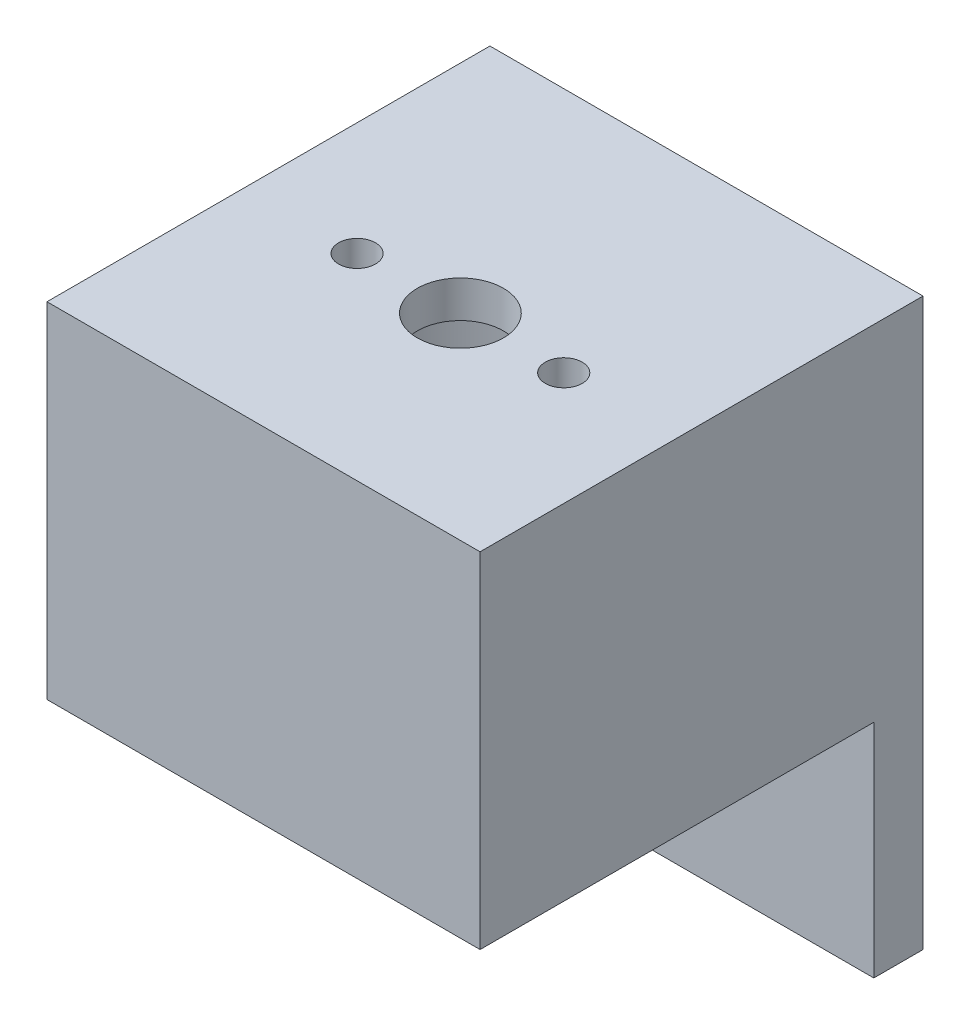
SolidWorks part; units mm, degrees
ref_plane "Спереди" through (0, 0, 0) normal (0, 0, 1) x (1, 0, 0)
ref_plane "Сверху" through (0, 0, 0) normal (0, 1, 0) x (1, 0, 0)
ref_plane "Справа" through (0, 0, 0) normal (1, 0, 0) x (0, 0, -1)
sketch "Эскиз1" plane through (0, 0, 0) normal (0, 0, 1) x (1, 0, 0)
  line L1 (-17.6, -21.5) -> (17.6, -21.5)
  line L2 (-17.6, -21.5) -> (-17.6, 21.5)
  line L3 (-17.6, 21.5) -> (17.6, 21.5)
  line L4 (17.6, -21.5) -> (17.6, 21.5)
  line L5 (-17.6, -21.5) -> (17.6, 21.5) construction
  line L6 (-17.6, 21.5) -> (17.6, -21.5) construction
  point P0 (0, 0)
  dimension "D1" = 35.2
  dimension "D2" = 43
extrude "Бобышка-Вытянуть1" add sketch "Эскиз1" along normal blind 4
sketch "Эскиз2" plane through (0, 0, 4) normal (0, 0, 1) x (1, 0, 0)
  line L0 (17.6, -21.5) -> (17.6, 21.5) construction
  line L1 (-17.6, 21.5) -> (17.6, 21.5)
  line L2 (-17.6, 21.5) -> (-17.6, -3.5)
  line L3 (-17.6, -3.5) -> (17.6, -3.5)
  line L4 (17.6, 21.5) -> (17.6, -3.5)
  dimension "D1" = 25
extrude "Бобышка-Вытянуть2" add sketch "Эскиз2" along normal blind 32
sketch "Эскиз4" plane through (0, -3.5, 0) normal (0, -1, 0) x (1, 0, 0)
  line L0 (17.6, 4) -> (-17.6, 36) construction
  line L1 (-17.6, 36) -> (17.6, 36) construction
  line L2 (-17.6, 36) -> (-17.6, 4) construction
  line L3 (17.6, 36) -> (-17.6, 4) construction
  circle A0 centre (0, 20) radius 12.5
extrude "Вырез-Вытянуть1" cut sketch "Эскиз4" against normal blind 32
sketch "Эскиз6" plane through (0, 0, 4) normal (0, 0, 1) x (1, 0, 0)
  line L0 (0, -3.5) -> (0, -21.5) construction
  line L1 (-17.6, -3.5) -> (17.6, -3.5) construction
  line L2 (-17.6, -21.5) -> (17.6, -21.5) construction
  circle A0 centre (0, -7.5) radius 2
  circle A1 centre (0, -17.5) radius 2
  dimension "D2" = 4
  dimension "D3" = 4
  dimension "D1" = 4
  dimension "D4" = 10
extrude "Вырез-Вытянуть2" cut sketch "Эскиз6" against normal blind 32
sketch "Эскиз7" plane through (0, 21.5, 0) normal (0, 1, 0) x (1, 0, 0)
  line L1 (-17.6, 0) -> (17.6, 0)
  line L2 (-17.6, 0) -> (-17.6, -36)
  line L3 (-17.6, -36) -> (17.6, -36)
  line L4 (17.6, 0) -> (17.6, -36)
extrude "Бобышка-Вытянуть3" add sketch "Эскиз7" along normal blind 3
sketch "Эскиз8" plane through (0, 24.5, 0) normal (0, 1, 0) x (1, 0, 0)
  line L0 (17.6, -4) -> (-17.6, -36) construction
  line L1 (-17.6, 0) -> (-17.6, -36) construction
  line L2 (17.6, 0) -> (-17.6, 0) construction
  line L3 (17.6, -36) -> (-17.6, -36) construction
  line L4 (17.6, -36) -> (17.6, -4) construction
  line L5 (17.6, -4) -> (-17.6, -4) construction
  line L6 (-17.6, -36) -> (-17.6, -4) construction
  line L7 (17.6, -36) -> (-17.6, -4) construction
  line L8 (-17.6, -20) -> (17.6, -20) construction
  line L9 (0, -20) -> (8.4, -20) construction
  line L10 (0, -20) -> (-8.4, -20) construction
  circle A0 centre (0, -20) radius 3.5
  circle A1 centre (0, -20) radius 12.5 construction
  circle A2 centre (8.4, -20) radius 1.5
  circle A3 centre (-8.4, -20) radius 1.5
  dimension "D1" = 4
extrude "Вырез-Вытянуть3" cut sketch "Эскиз8" against normal blind 10
sketch "Эскиз9" plane through (0, 24.5, 0) normal (0, 1, 0) x (1, 0, 0)
